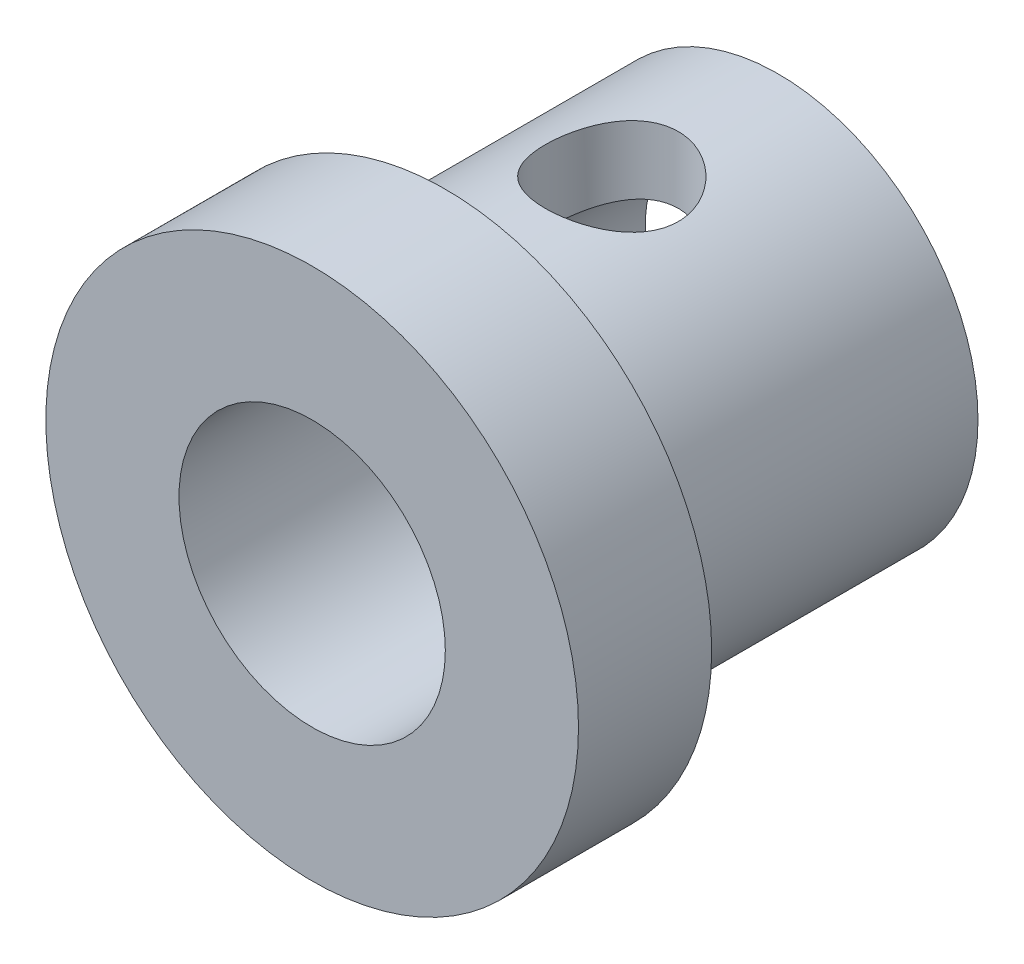
SolidWorks part; units mm, degrees
material "ASTM A36 Steel"
ref_plane "Front Plane" through (0, 0, 0) normal (0, 0, 1) x (1, 0, 0)
ref_plane "Top Plane" through (0, 0, 0) normal (0, 1, 0) x (1, 0, 0)
ref_plane "Right Plane" through (0, 0, 0) normal (1, 0, 0) x (0, 0, -1)
sketch "Sketch1" plane through (0, 0, 0) normal (1, 0, 0) x (0, 0, -1)
  line L0 (-4.5787, 0) -> (5.382, 0) construction
  line L1 (0, 4) -> (0, 2)
  line L2 (0, 2) -> (7, 2)
  line L3 (7, 2) -> (7, 3)
  line L4 (7, 3) -> (2, 3)
  line L5 (2, 3) -> (2, 4)
  line L6 (2, 4) -> (0, 4)
  dimension "D1" = 7
  dimension "D2" = 2
  dimension "D3" = 3
  dimension "D4" = 4
  dimension "D5" = 2
revolve "Revolve1" add sketch "Sketch1" angle 360 about L0
sketch "Sketch2" plane through (0, 0, 0) normal (0, 1, 0) x (1, 0, 0)
  line L0 (2, 7) -> (-2, 7) construction
  circle A0 centre (0, 4.5) radius 1
  dimension "D1" = 2
  dimension "D2" = 2.5
extrude "Cut-Extrude1" cut sketch "Sketch2" against normal through all both and the other way through all
